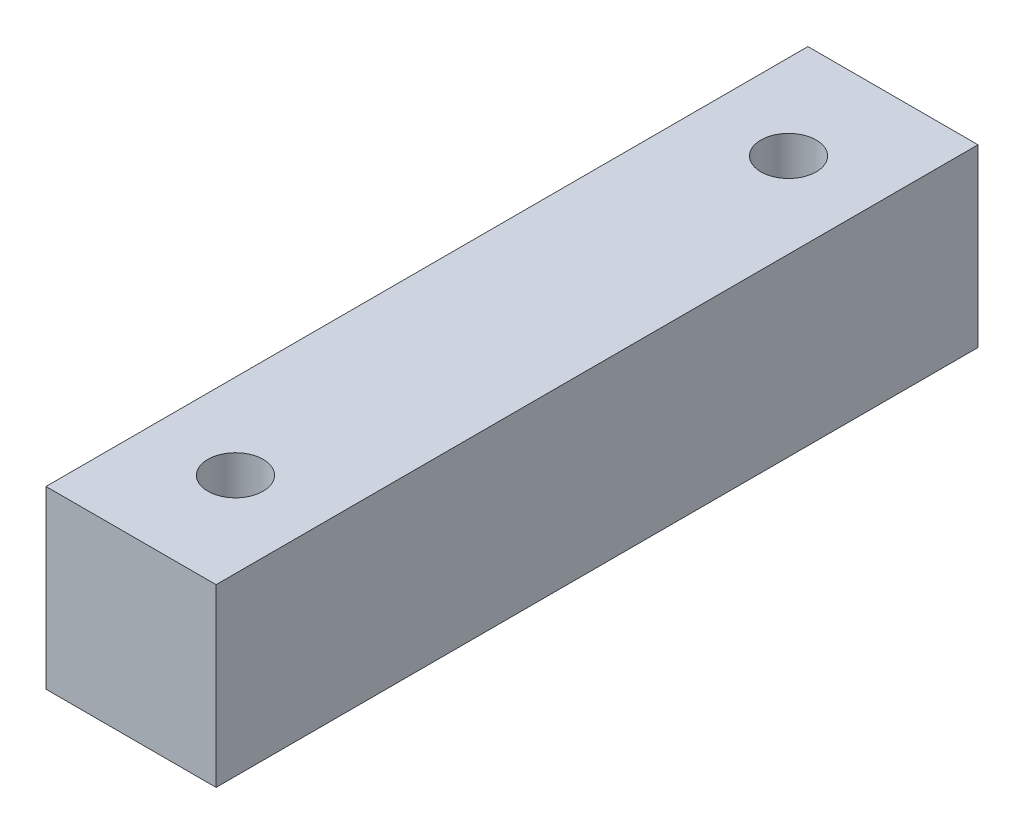
SolidWorks part; units mm, degrees
ref_plane "Front Plane" through (0, 0, 0) normal (0, 0, 1) x (1, 0, 0)
ref_plane "Top Plane" through (0, 0, 0) normal (0, 1, 0) x (1, 0, 0)
ref_plane "Right Plane" through (0, 0, 0) normal (1, 0, 0) x (0, 0, -1)
sketch "Sketch1" plane through (0, 0, 0) normal (0, 1, 0) x (1, 0, 0)
  line L1 (-29.0534, 42.2168) -> (-41.3534, 42.2168)
  line L2 (-29.0534, 42.2168) -> (-29.0534, -12.8832)
  line L3 (-29.0534, -12.8832) -> (-41.3534, -12.8832)
  line L4 (-41.3534, 42.2168) -> (-41.3534, -12.8832)
  dimension "D1" = 12.3
  dimension "D2" = 55.1
extrude "Boss-Extrude1" add sketch "Sketch1" along normal blind 12.7
sketch "Sketch2" plane through (0, 12.7, 0) normal (0, 1, 0) x (1, 0, 0)
  line L0 (-35.2034, 42.2168) -> (-35.2034, -12.8832) construction
  line L4 (-29.0534, -12.8832) -> (-29.0534, 42.2168)
  line L5 (-29.0534, 42.2168) -> (-41.3534, 42.2168)
  line L6 (-41.3534, 42.2168) -> (-41.3534, -12.8832)
  line L7 (-41.3534, -12.8832) -> (-29.0534, -12.8832)
  line L8 (-29.0534, -12.8832) -> (-29.0534, 42.2168)
  line L9 (-29.0534, 42.2168) -> (-41.3534, 42.2168)
  line L10 (-41.3534, 42.2168) -> (-41.3534, -12.8832)
  line L11 (-41.3534, -12.8832) -> (-29.0534, -12.8832)
  circle A0 centre (-35.2034, -5.3332) radius 2
  circle A1 centre (-35.2034, 34.6668) radius 2
  point P10 (0, 0)
  point P12 (-40.2987, -13.0686)
  dimension "D4" = 4
  dimension "D5" = 4
  dimension "D2" = 40
  dimension "D3" = 7.55
  dimension "D1" = 0
extrude "Cut-Extrude1" cut sketch "Sketch2" against normal blind 14 contours A1 | A0
